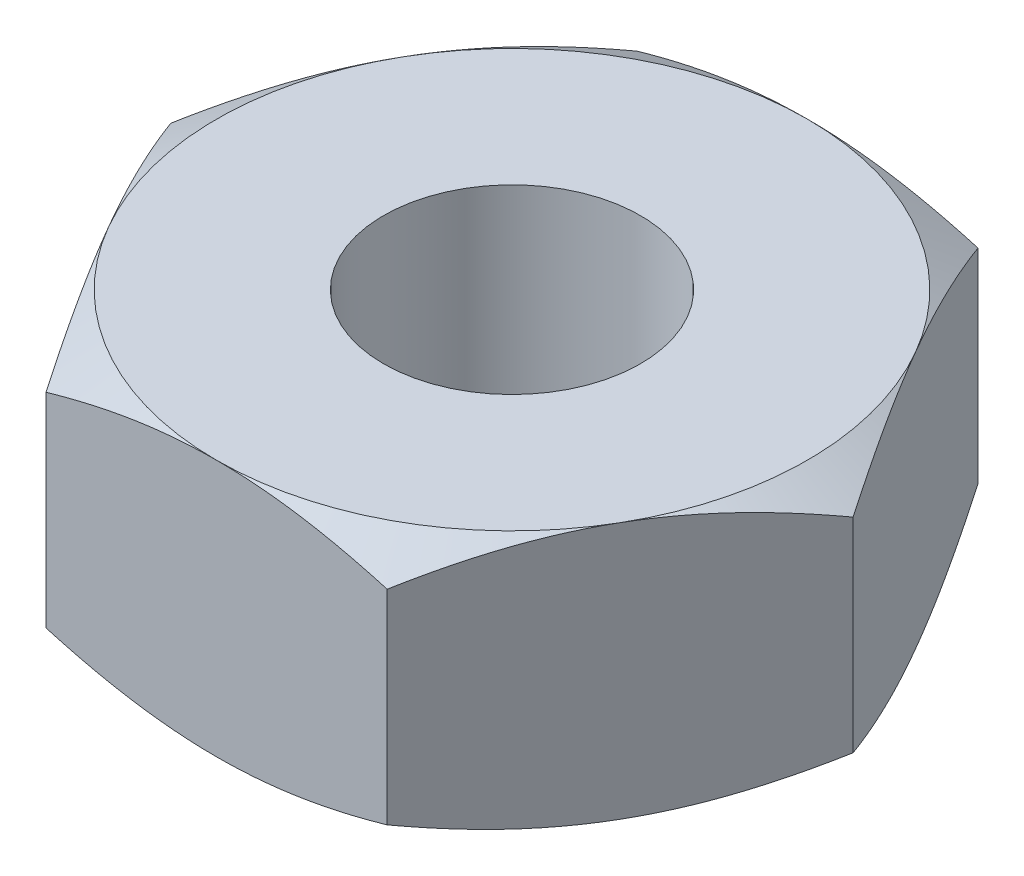
SolidWorks part; units mm, degrees
ref_plane "Front Plane" through (0, 0, 0) normal (0, 0, 1) x (1, 0, 0)
ref_plane "Top Plane" through (0, 0, 0) normal (0, 1, 0) x (1, 0, 0)
ref_plane "Right Plane" through (0, 0, 0) normal (1, 0, 0) x (0, 0, -1)
sketch "Sketch1" plane through (0, 0, 0) normal (0, 1, 0) x (1, 0, 0)
  line L1 (6.6395, 0) -> (3.3198, 5.75)
  line L2 (3.3198, 5.75) -> (-3.3198, 5.75)
  line L3 (-3.3198, 5.75) -> (-6.6395, 0)
  line L4 (-6.6395, 0) -> (-3.3198, -5.75)
  line L5 (-3.3198, -5.75) -> (3.3198, -5.75)
  line L6 (3.3198, -5.75) -> (6.6395, 0)
  circle A0 centre (0, 0) radius 5.75 construction
extrude "Boss-Extrude1" add sketch "Sketch1" along normal blind 5
sketch "Sketch2" plane through (0, 5, 0) normal (0, 1, 0) x (1, 0, 0)
  circle A0 centre (0, 0) radius 5.75
extrude "Cut-Extrude1" cut sketch "Sketch2" against normal blind 5 draft 60 flip side to cut
sketch "Sketch3" plane through (0, 0, 0) normal (0, -1, 0) x (1, 0, 0)
  circle A0 centre (0, 0) radius 5.75
extrude "Cut-Extrude2" cut sketch "Sketch3" against normal blind 5 draft 60 flip side to cut
hole_wizard "M6 Tapped Hole1" positions "Sketch4" profile "Sketch5" tap size "M6" standard "ISO"
sketch "Sketch4" plane through (0, 5, 0) normal (0, 1, 0) x (1, 0, 0)
  point P0 (0, 0)
sketch "Sketch5" plane through (0, 5, 0) normal (1, 0, 0) x (0, 0, 1)
  line L0 (0, 0) -> (0, 17)
  line L1 (0, 17) -> (2.5, 17)
  line L2 (2.5, 17) -> (2.5, 0)
  line L5 (2.5, 0) -> (0, 0)
  line L10 (0, 17) -> (-2.5, 17) construction
  line L11 (0, -6.35) -> (0, 107.95) construction
  dimension "Tap Drill Dia." = 5
  dimension "Tap Drill Depth" = 17
  dimension "Drill Angle" = 180
cosmetic thread "Hole Thread1" parameters "D1"=12, "D2"=6
